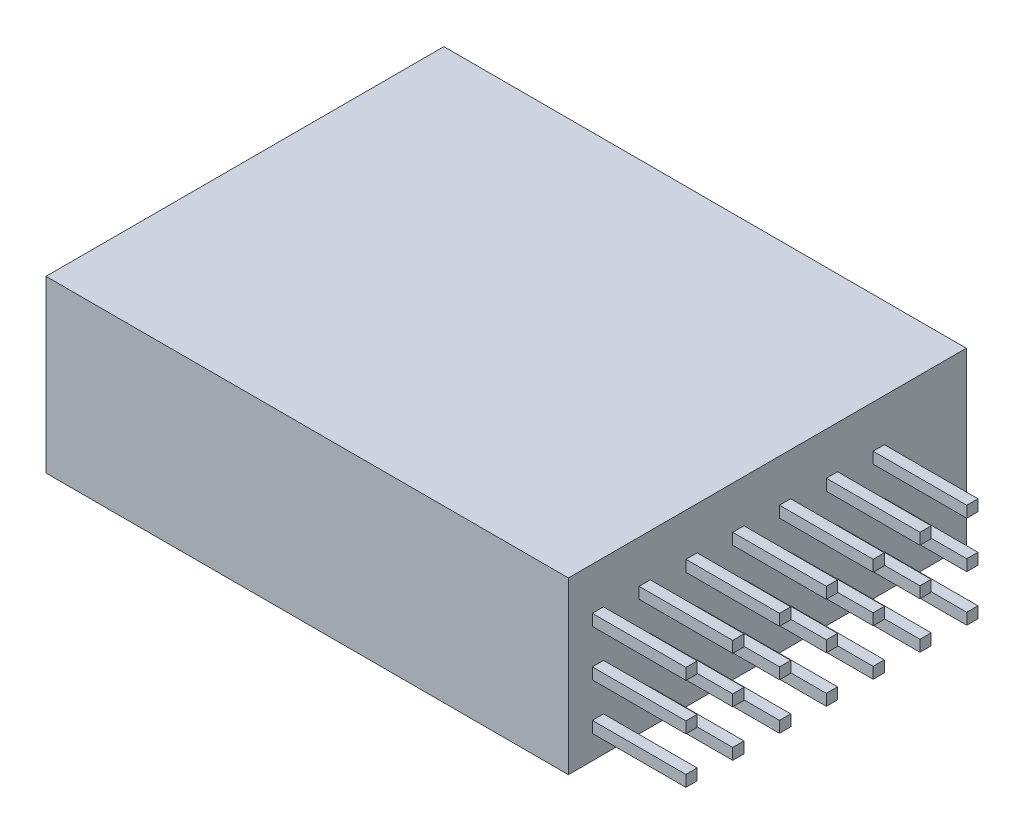
SolidWorks part; units mm, degrees
material "Spektrum AR6115e"
ref_plane "Front Plane" through (0, 0, 0) normal (0, 0, 1) x (1, 0, 0)
ref_plane "Top Plane" through (0, 0, 0) normal (0, 1, 0) x (1, 0, 0)
ref_plane "Right Plane" through (0, 0, 0) normal (1, 0, 0) x (0, 0, -1)
sketch "Sketch1" plane through (0, 0, 0) normal (0, 1, 0) x (1, 0, 0)
  line L1 (0, 0) -> (28.3464, 0)
  line L2 (0, 0) -> (0, 21.59)
  line L3 (0, 21.59) -> (28.3464, 21.59)
  line L4 (28.3464, 0) -> (28.3464, 21.59)
  dimension "D1" = 28.3464
  dimension "D2" = 21.59
extrude "Boss-Extrude1" add sketch "Sketch1" along normal blind 9.2456
sketch "Sketch2" plane through (28.3464, 0, 0) normal (1, 0, 0) x (0, 0, -1)
  line L0 (0, 9.2456) -> (0, 0) construction
  line L1 (1.905, 6.9342) -> (1.2954, 6.9342)
  line L2 (1.905, 6.9342) -> (1.905, 6.3246)
  line L3 (1.905, 6.3246) -> (1.2954, 6.3246)
  line L4 (1.2954, 6.9342) -> (1.2954, 6.3246)
  line L5 (1.2954, 1.905) -> (1.905, 1.905)
  line L6 (1.2954, 1.905) -> (1.2954, 1.2954)
  line L7 (1.2954, 1.2954) -> (1.905, 1.2954)
  line L8 (1.905, 1.905) -> (1.905, 1.2954)
  line L9 (1.905, 4.4196) -> (1.2954, 4.4196)
  line L10 (1.905, 4.4196) -> (1.905, 3.81)
  line L11 (1.905, 3.81) -> (1.2954, 3.81)
  line L12 (1.2954, 4.4196) -> (1.2954, 3.81)
  line L14 (0, 0) -> (21.59, 0) construction
  dimension "D1" = 0.6096
  dimension "D2" = 1.905
  dimension "D3" = 1.905
  dimension "D4" = 1.905
  dimension "D5" = 1.905
extrude "Boss-Extrude2" add sketch "Sketch2" along normal blind 5.08
pattern_linear "LPattern1" count 7 spacing 2.54 along (0, 0, -1) of "Boss-Extrude2"
